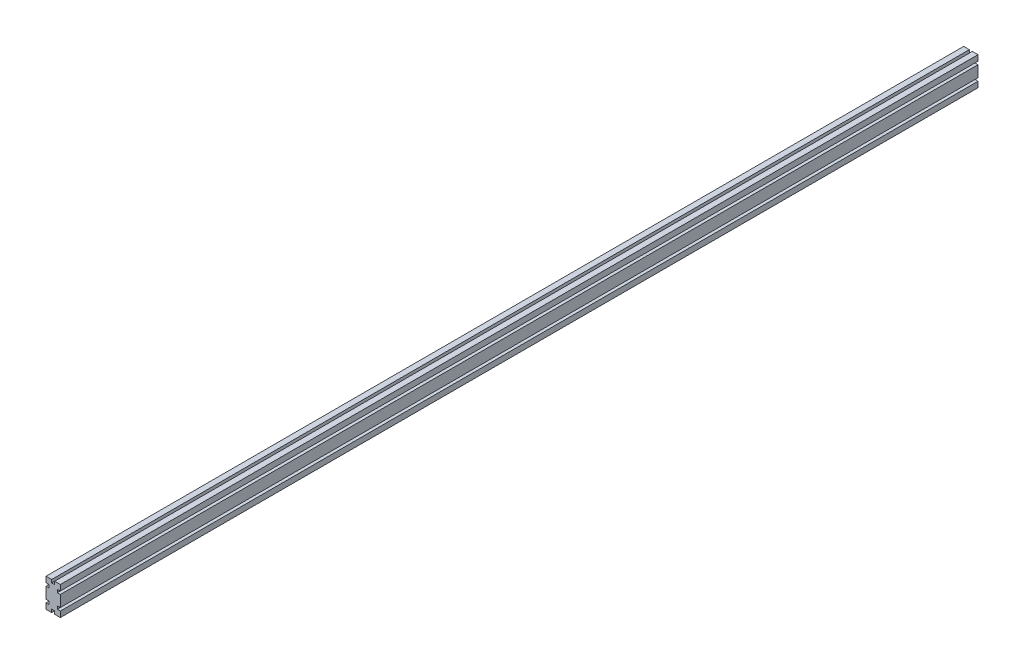
SolidWorks part; units mm, degrees
ref_plane "Front Plane" through (0, 0, 0) normal (0, 0, 1) x (1, 0, 0)
ref_plane "Top Plane" through (0, 0, 0) normal (0, 1, 0) x (1, 0, 0)
ref_plane "Right Plane" through (0, 0, 0) normal (1, 0, 0) x (0, 0, -1)
sketch "Sketch1" plane through (0, 0, 0) normal (0, 0, 1) x (1, 0, 0)
  line L0 (-19.05, -38.1) -> (-4, -38.1)
  line L1 (-4, -38.1) -> (-4, -30.1)
  line L2 (-4, -30.1) -> (4, -30.1)
  line L3 (4, -30.1) -> (4, -38.1)
  line L4 (4, -38.1) -> (19.05, -38.1)
  line L5 (19.05, -38.1) -> (19.05, -23.05)
  line L6 (19.05, -23.05) -> (11.05, -23.05)
  line L7 (11.05, -23.05) -> (11.05, -15.05)
  line L8 (11.05, -15.05) -> (19.05, -15.05)
  line L9 (19.05, -15.05) -> (19.05, 15.05)
  line L10 (19.05, 15.05) -> (11.05, 15.05)
  line L11 (11.05, 15.05) -> (11.05, 23.05)
  line L12 (11.05, 23.05) -> (19.05, 23.05)
  line L13 (19.05, 23.05) -> (19.05, 38.1)
  line L14 (19.05, 38.1) -> (4, 38.1)
  line L15 (4, 38.1) -> (4, 30.1)
  line L16 (4, 30.1) -> (-4, 30.1)
  line L17 (-4, 30.1) -> (-4, 38.1)
  line L18 (-4, 38.1) -> (-19.05, 38.1)
  line L19 (-19.05, 38.1) -> (-19.05, 23.05)
  line L20 (-19.05, 23.05) -> (-11.05, 23.05)
  line L21 (-11.05, 23.05) -> (-11.05, 15.05)
  line L22 (-11.05, 15.05) -> (-19.05, 15.05)
  line L23 (-19.05, 15.05) -> (-19.05, -15.05)
  line L24 (-19.05, -15.05) -> (-11.05, -15.05)
  line L25 (-11.05, -15.05) -> (-11.05, -23.05)
  line L26 (-11.05, -23.05) -> (-19.05, -23.05)
  line L27 (-19.05, -23.05) -> (-19.05, -38.1)
extrude "Profile" add sketch "Sketch1" along normal blind 2438.4
equation "\"length\" = 2438.4mm"
equation "\"D1@Profile\" = \"length\""
